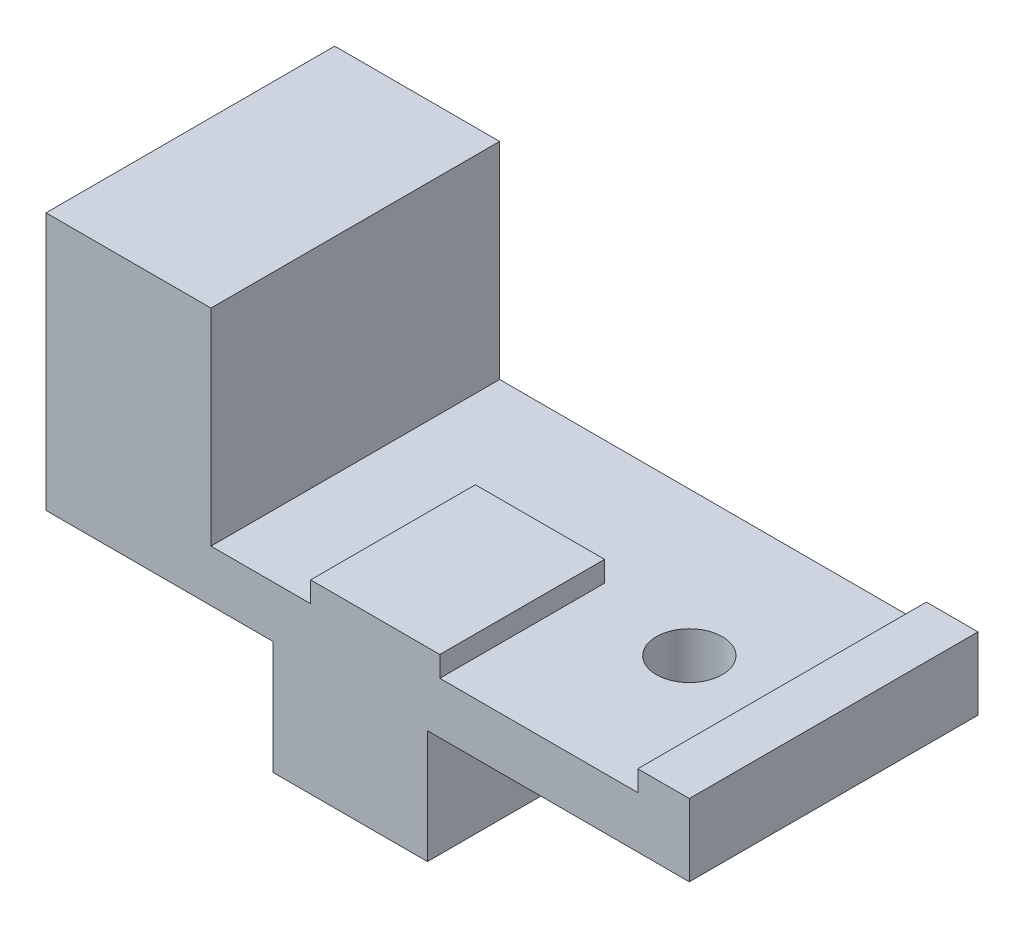
SolidWorks part; units mm, degrees
ref_plane "前视基准面" through (0, 0, 0) normal (0, 0, 1) x (1, 0, 0)
ref_plane "上视基准面" through (0, 0, 0) normal (0, 1, 0) x (1, 0, 0)
ref_plane "右视基准面" through (0, 0, 0) normal (1, 0, 0) x (0, 0, -1)
sketch "草图1" plane through (0, 0, 0) normal (0, 1, 0) x (1, 0, 0)
  line L1 (-15.6, 7) -> (15.6, 7)
  line L2 (-15.6, 7) -> (-15.6, -7)
  line L3 (-15.6, -7) -> (15.6, -7)
  line L4 (15.6, 7) -> (15.6, -7)
  line L5 (-15.6, 7) -> (15.6, -7) construction
  line L6 (-15.6, -7) -> (15.6, 7) construction
  point P0 (0, 0)
  dimension "D1" = 31.2
  dimension "D2" = 14
extrude "凸台-拉伸1" add sketch "草图1" along normal blind 2.5
sketch "草图2" plane through (0, 2.5, 0) normal (0, 1, 0) x (1, 0, 0)
  line L0 (15.6, 7) -> (-15.6, 7) construction
  line L1 (-15.6, -7) -> (-7.6, -7)
  line L2 (-15.6, -7) -> (-15.6, 7)
  line L3 (-15.6, 7) -> (-7.6, 7)
  line L4 (-7.6, -7) -> (-7.6, 7)
  dimension "D1" = 8
extrude "凸台-拉伸2" add sketch "草图2" along normal blind 10
sketch "草图3" plane through (0, 0, 0) normal (0, -1, 0) x (1, 0, 0)
  line L0 (-15.6, 7) -> (15.6, 7) construction
  line L1 (-4.6, 7) -> (2.9, 7)
  line L2 (-4.6, 7) -> (-4.6, -0.5)
  line L3 (-4.6, -0.5) -> (2.9, -0.5)
  line L4 (2.9, 7) -> (2.9, -0.5)
  line L5 (-15.6, -7) -> (-15.6, 7) construction
  dimension "D1" = 11
  dimension "D2" = 7.5
  dimension "D3" = 7.5
extrude "凸台-拉伸3" add sketch "草图3" along normal blind 5.5
hole_wizard "M3 间隙孔1" positions "草图6" profile "草图7" hole size "M3" standard "ISO" end condition up to next
sketch "草图6" plane through (0, 2.5, 0) normal (0, 1, 0) x (1, 0, 0)
  line L0 (-9.9, 0) -> (9.9, 0) construction
  line L1 (15.6, -7) -> (15.6, 7) construction
  point P0 (8.6, 0)
  dimension "D1" = 7
sketch "草图7" plane through (8.6, 2.5, 0) normal (1, 0, 0) x (0, 0, 1)
  line L0 (0, 0) -> (0, 2.5)
  line L1 (0, 2.5) -> (1.6, 2.5)
  line L2 (1.6, 2.5) -> (1.6, 0)
  line L5 (1.6, 0) -> (0, 0)
  line L11 (0, -6.35) -> (0, 107.95) construction
  dimension "通孔孔直径" = 3.2
  dimension "通孔孔深度" = 2.5
sketch "草图9" plane through (0, 2.5, 0) normal (0, 1, 0) x (1, 0, 0)
  line L0 (-7.6, -7) -> (15.6, -7) construction
  line L1 (3.5, -7) -> (-2.7667, -7)
  line L2 (3.5, -7) -> (3.5, 0.9911)
  line L3 (3.5, 0.9911) -> (-2.7667, 0.9911)
  line L4 (-2.7667, -7) -> (-2.7667, 0.9911)
  circle A0 centre (8.6, 0) radius 1.6 construction
  dimension "D1" = 5.1
extrude "凸台-拉伸7" add sketch "草图9" along normal blind 1
sketch "草图10" plane through (0, 2.5, 0) normal (0, -1, 0) x (1, 0, 0)
  line L0 (15.6, -7) -> (-15.6, -7) construction
  line L1 (15.6, 7) -> (13.1, 7)
  line L2 (15.6, 7) -> (15.6, -7)
  line L3 (15.6, -7) -> (13.1, -7)
  line L4 (13.1, 7) -> (13.1, -7)
  dimension "D1" = 2.5
extrude "凸台-拉伸8" add sketch "草图10" against normal blind 1
